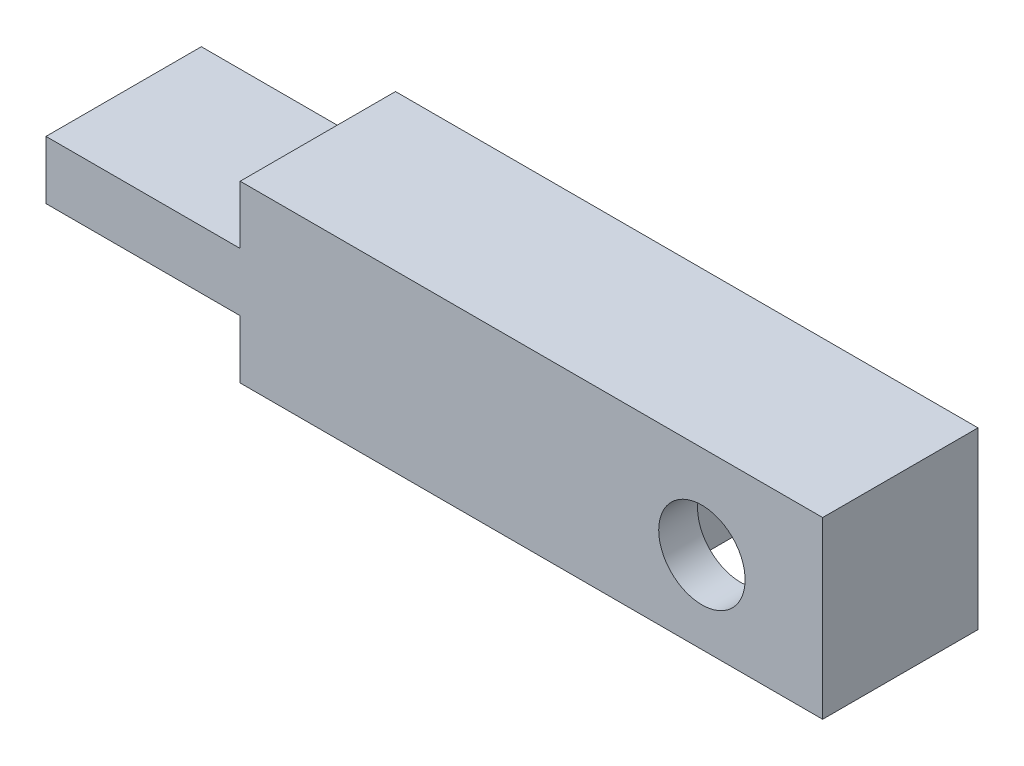
SolidWorks part; units mm, degrees
ref_plane "Alzado" through (0, 0, 0) normal (0, 0, 1) x (1, 0, 0)
ref_plane "Planta" through (0, 0, 0) normal (0, 1, 0) x (1, 0, 0)
ref_plane "Vista lateral" through (0, 0, 0) normal (1, 0, 0) x (0, 0, -1)
sketch "Croquis1" plane through (0, 0, 0) normal (0, 1, 0) x (1, 0, 0)
  line L1 (-175, -20) -> (175, -20)
  line L2 (-175, -20) -> (-175, 20)
  line L3 (-175, 20) -> (175, 20)
  line L4 (175, -20) -> (175, 20)
  line L5 (-175, -20) -> (175, 20) construction
  line L6 (-175, 20) -> (175, -20) construction
  point P0 (0, 0)
  dimension "D1" = 350
  dimension "D2" = 40
extrude "Saliente-Extruir1" add sketch "Croquis1" along normal blind 45
sketch "Croquis2" plane through (0, 0, -20) normal (0, 0, -1) x (-1, 0, 0)
  line L0 (-175, 0) -> (175, 0) construction
  line L1 (-165, 0) -> (-122.8, 0)
  line L2 (-165, 0) -> (-165, 42.2)
  line L3 (-165, 42.2) -> (-122.8, 42.2)
  line L4 (-122.8, 0) -> (-122.8, 42.2)
  line L5 (-175, 45) -> (-175, 0) construction
  dimension "D1" = 10
  dimension "D2" = 42.2
  dimension "D3" = 42.2
extrude "Cortar-Extruir1" cut sketch "Croquis2" against normal blind 30
sketch "Croquis3" plane through (0, 0, 10) normal (0, 0, -1) x (-1, 0, 0)
  line L0 (-165, 42.2) -> (-122.8, 0) construction
  line L4 (-165, 42.2) -> (-165, 0)
  line L5 (-165, 0) -> (-122.8, 0)
  line L6 (-122.8, 0) -> (-122.8, 42.2)
  line L7 (-122.8, 42.2) -> (-165, 42.2)
  line L8 (-165, 42.2) -> (-165, 0)
  line L9 (-165, 0) -> (-122.8, 0)
  line L10 (-122.8, 0) -> (-122.8, 42.2)
  line L11 (-122.8, 42.2) -> (-165, 42.2)
  circle A0 centre (-143.9, 21.1) radius 11.125
  dimension "D2" = 22.25
  dimension "D1" = 0
extrude "Cortar-Extruir2" cut sketch "Croquis3" against normal blind 30 contours A0
mirror "Simetría1" about plane through (0, 0, 0) normal (1, 0, 0) of "Cortar-Extruir2", "Cortar-Extruir1"
sketch "Croquis4" plane through (0, 0, 20) normal (0, 0, 1) x (1, 0, 0)
  line L1 (25, 0) -> (25, 15)
  line L2 (-175, 0) -> (175, 0) construction
  line L3 (25, 15) -> (-25, 15)
  line L4 (-25, 15) -> (-25, 30)
  line L5 (-25, 30) -> (25, 30)
  line L6 (25, 30) -> (25, 45)
  line L7 (-175, 45) -> (175, 45) construction
  line L12 (-175, 0) -> (175, 0)
  line L13 (175, 0) -> (175, 45)
  line L14 (175, 45) -> (-175, 45)
  line L15 (-175, 45) -> (-175, 0)
  line L16 (-175, 0) -> (175, 0)
  line L17 (175, 0) -> (175, 45)
  line L18 (175, 45) -> (-175, 45)
  line L19 (-175, 45) -> (-175, 0)
  circle M8 centre (-143.9, 21.1) radius 11.125
  line M10 (-175, 0) -> (175, 0)
  line M12 (175, 45) -> (-175, 45)
  line M13 (-175, 45) -> (-175, 0)
  dimension "D1" = 0
  dimension "D2" = 50
  dimension "D3" = 25
  dimension "D4" = 15
  dimension "D5" = 15
  dimension "D6" = 25
extrude "Cortar-Extruir4" cut sketch "Croquis4" against normal through all contours L5 L6 L1 L3 L4 M12 M13 M10 M8
